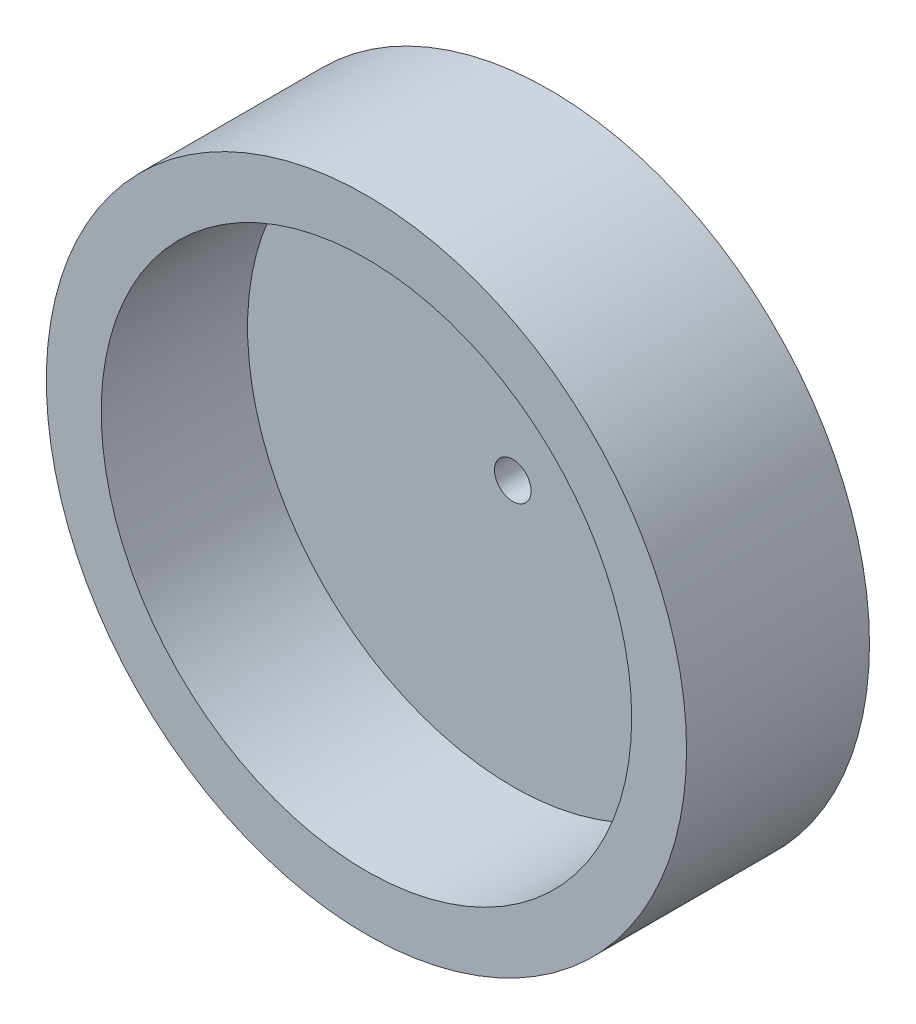
SolidWorks part; units mm, degrees
material "Natural Rubber"
ref_plane "Front Plane" through (0, 0, 0) normal (0, 0, 1) x (1, 0, 0)
ref_plane "Top Plane" through (0, 0, 0) normal (0, 1, 0) x (1, 0, 0)
ref_plane "Right Plane" through (0, 0, 0) normal (1, 0, 0) x (0, 0, -1)
sketch "Sketch1" plane through (0, 0, 0) normal (0, 0, 1) x (1, 0, 0)
  circle A0 centre (0, 0) radius 17.5
  dimension "D1" = 35
extrude "Boss-Extrude1" add sketch "Sketch1" along normal blind 2
sketch "Sketch2" plane through (0, 0, 2) normal (0, 0, 1) x (1, 0, 0)
  circle A0 centre (0, 0) radius 17.5
  circle A1 centre (0, 0) radius 14.5
  circle A2 centre (0, 0) radius 17.5 construction
  dimension "D2" = 3
extrude "Boss-Extrude2" add sketch "Sketch2" along normal blind 8
sketch "Sketch3" plane through (0, 0, 2) normal (0, 0, 1) x (1, 0, 0)
  circle A0 centre (0, 0) radius 1
  dimension "D1" = 2
extrude "Cut-Extrude1" cut sketch "Sketch3" against normal through all
